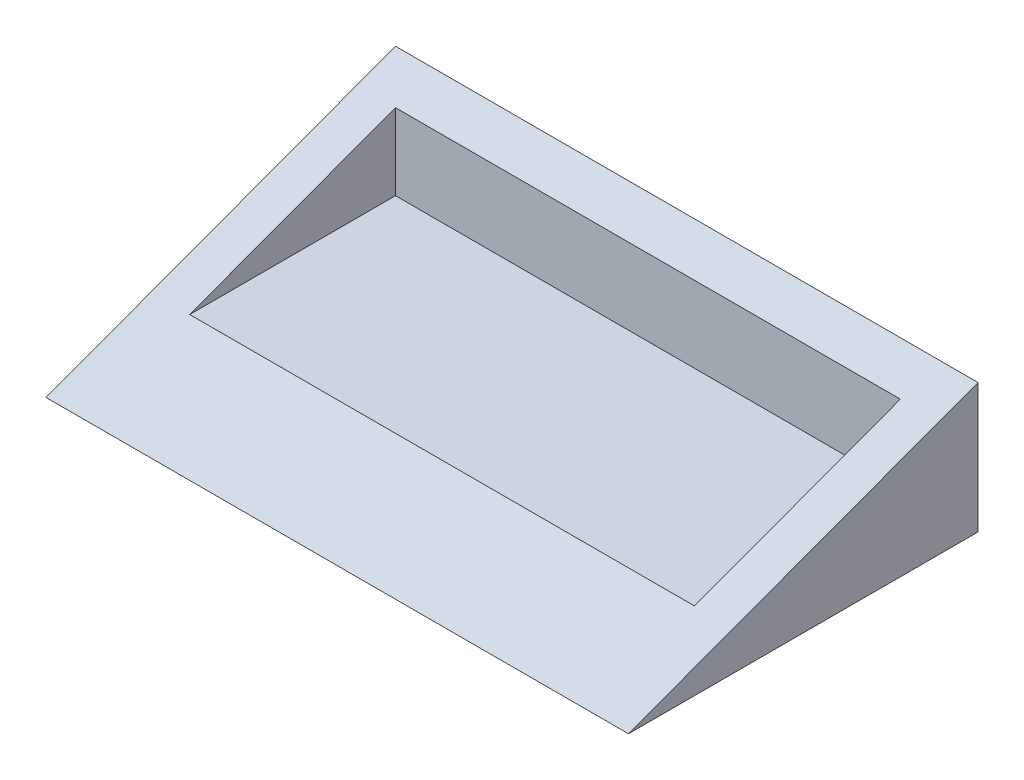
SolidWorks part; units mm, degrees
ref_plane "Alzado" through (0, 0, 0) normal (0, 0, 1) x (1, 0, 0)
ref_plane "Planta" through (0, 0, 0) normal (0, 1, 0) x (1, 0, 0)
ref_plane "Vista lateral" through (0, 0, 0) normal (1, 0, 0) x (0, 0, -1)
sketch "Croquis1" plane through (0, 0, 0) normal (1, 0, 0) x (0, 0, -1)
  line L0 (0, 0) -> (27, 10)
  line L1 (27, 10) -> (27, 0)
  line L2 (27, 0) -> (0, 0)
  dimension "D1" = 10
  dimension "D2" = 27
extrude "Saliente-Extruir1" add sketch "Croquis1" along normal blind 45
shell "Vaciado1" thickness 3
